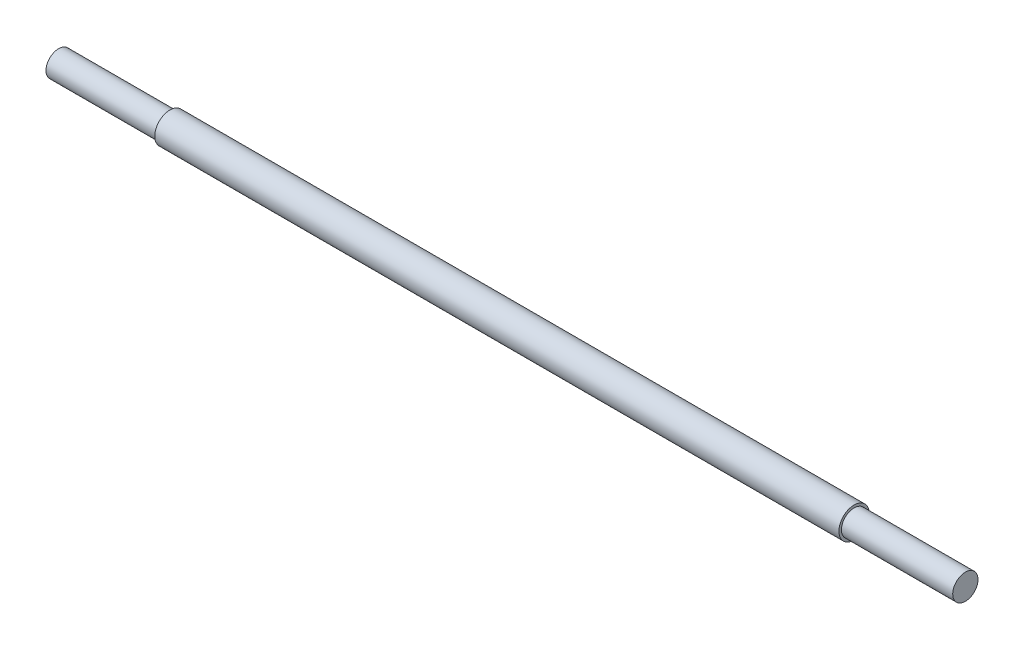
SolidWorks part; units mm, degrees
ref_plane "Front Plane" through (0, 0, 0) normal (0, 0, 1) x (1, 0, 0)
ref_plane "Top Plane" through (0, 0, 0) normal (0, 1, 0) x (1, 0, 0)
ref_plane "Right Plane" through (0, 0, 0) normal (1, 0, 0) x (0, 0, -1)
sketch "Sketch1" plane through (0, 0, 0) normal (0, 0, 1) x (1, 0, 0)
  line L0 (0, 0) -> (89.63, 0)
  line L1 (89.63, 0) -> (89.63, 1.25)
  line L2 (89.63, 1.25) -> (78.63, 1.25)
  line L3 (78.63, 1.25) -> (78.63, 1.5)
  line L4 (78.63, 1.5) -> (11, 1.5)
  line L5 (11, 1.5) -> (11, 1.25)
  line L6 (11, 1.25) -> (0, 1.25)
  line L7 (0, 1.25) -> (0, 0)
  dimension "D1" = 67.63
  dimension "D2" = 11
  dimension "D3" = 11
  dimension "D4" = 1.25
  dimension "D5" = 1.5
revolve "Revolve1" add sketch "Sketch1" angle 360 about L0
